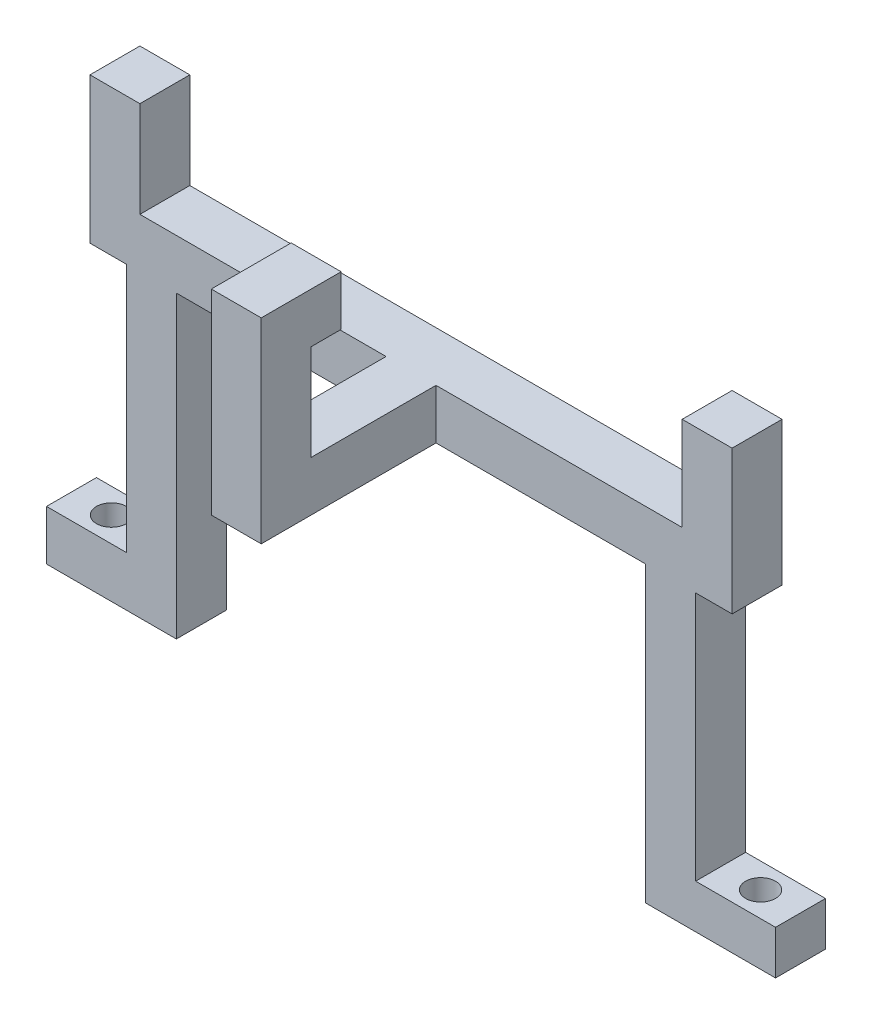
SolidWorks part; units mm, degrees
ref_plane "Front Plane" through (0, 0, 0) normal (0, 0, 1) x (1, 0, 0)
ref_plane "Top Plane" through (0, 0, 0) normal (0, 1, 0) x (1, 0, 0)
ref_plane "Right Plane" through (0, 0, 0) normal (1, 0, 0) x (0, 0, -1)
sketch "Sketch1" plane through (0, 0, 0) normal (0, 0, 1) x (1, 0, 0)
  line L0 (0, 0) -> (0, 25)
  line L1 (-3.65, 25) -> (-3.65, 39.6)
  line L2 (0, 25) -> (-3.65, 25)
  line L3 (-3.65, 39.6) -> (1.35, 39.6)
  line L4 (1.35, 30) -> (5, 30)
  line L8 (1.35, 39.6) -> (1.35, 30)
  line L9 (5, 30) -> (5, -5)
  line L10 (5, -5) -> (-8, -5)
  line L11 (-8, -5) -> (-8, 0)
  line L12 (-8, 0) -> (0, 0)
  dimension "D1" = 5
  dimension "D2" = 25
  dimension "D3" = 5
  dimension "D4" = 3.65
  dimension "D5" = 5
  dimension "D6" = 35
  dimension "D7" = 9.6
  dimension "D8" = 5
  dimension "D9" = 8
extrude "Boss-Extrude1" add sketch "Sketch1" along normal blind 5
sketch "Sketch2" plane through (0, 0, 0) normal (0, 1, 0) x (1, 0, 0)
  line L0 (-4, 0) -> (-4, -5) construction
  line L1 (0, 0) -> (-8, 0) construction
  line L2 (0, -5) -> (-8, -5) construction
  line L3 (-4, -5) -> (-4, 0) construction
  circle A0 centre (-4, -2.5) radius 1.5
extrude "Cut-Extrude1" cut sketch "Sketch2" against normal through all
sketch "Sketch3" plane through (5, 0, 0) normal (1, 0, 0) x (0, 0, -1)
  line L0 (-5, 30) -> (-5, 25)
  line L1 (-5, -5) -> (-5, 30) construction
  line L2 (-5, 25) -> (0, 25)
  line L3 (0, -5) -> (0, 30) construction
  line L4 (0, 25) -> (0, 30)
  line L5 (0, 30) -> (-5, 30)
  dimension "D1" = 5
  dimension "D2" = 5
extrude "Boss-Extrude2" add sketch "Sketch3" along normal blind 47
sketch "Sketch4" plane through (0, 0, 0) normal (0, 0, -1) x (-1, 0, 0)
  line L0 (-52, 30) -> (-55.65, 30)
  line L1 (-55.65, 30) -> (-55.65, 39.3793)
  line L2 (-55.65, 39.3793) -> (-60.65, 39.3793)
  line L3 (-60.65, 39.3793) -> (-60.65, 25)
  line L4 (-60.65, 25) -> (-57, 25)
  line L5 (-57, 25) -> (-57, 0)
  line L6 (-57, 0) -> (-65, 0)
  line L7 (-65, 0) -> (-65, -4.3959)
  line L8 (-65, -4.3959) -> (-52, -4.3959)
  line L9 (-52, -4.3959) -> (-52, 25)
  line L10 (-52, 25) -> (-5, 25) construction
  line L11 (-52, 25) -> (-52, 30) construction
  line L12 (-52, 25) -> (-52, 30)
  line L13 (-5, -5) -> (-5, 25) construction
  line L14 (3.65, 39.6) -> (3.65, 25) construction
  line L16 (0, 25) -> (0, 0) construction
  dimension "D1" = 8.65
  dimension "D2" = 8.65
  dimension "D3" = 5
  dimension "D4" = 5
  dimension "D5" = 5
  dimension "D6" = 13
extrude "Boss-Extrude3" add sketch "Sketch4" against normal blind 5
sketch "Sketch5" plane through (0, 0, 0) normal (0, 1, 0) x (1, 0, 0)
  line L3 (57, -5) -> (57, 0) construction
  circle A0 centre (61, -2.5) radius 1.5
  dimension "D1" = 4
extrude "Cut-Extrude2" cut sketch "Sketch5" against normal through all
sketch "Sketch7" plane through (0, 0, 5) normal (0, 0, 1) x (1, 0, 0)
  line L0 (28.5, 30) -> (28.5, 25) construction
  line L1 (55.65, 30) -> (1.35, 30) construction
  line L2 (52, 25) -> (5, 25) construction
  line L3 (28.5, 30) -> (31, 30)
  line L4 (31, 30) -> (31, 25)
  line L5 (31, 25) -> (26, 25)
  line L6 (26, 25) -> (26, 30)
  line L7 (26, 30) -> (28.5, 30)
  dimension "D1" = 2.5
  dimension "D2" = 2.5
extrude "Boss-Extrude4" add sketch "Sketch7" along normal blind 12.5
sketch "Sketch10" plane through (0, 25, 0) normal (0, -1, 0) x (-1, 0, 0)
  line L0 (-31, -17.5) -> (-31, -22.5)
  line L1 (-31, -22.5) -> (-26, -22.5)
  line L2 (-26, -22.5) -> (-26, -17.5)
  line L11 (-5, -5) -> (-5, 0)
  line L12 (-5, 0) -> (-52, 0)
  line L13 (-52, 0) -> (-52, -5)
  line L14 (-52, -5) -> (-31, -5)
  line L15 (-31, -5) -> (-31, -17.5)
  line L16 (-31, -17.5) -> (-26, -17.5)
  line L17 (-26, -17.5) -> (-26, -5)
  line L18 (-26, -5) -> (-5, -5)
  line L24 (-31, -17.5) -> (-26, -17.5)
  dimension "D1" = 5
  dimension "D2" = 5
  dimension "D3" = 0
extrude "Boss-Extrude5" add sketch "Sketch10" against normal blind 14.6
sketch "Sketch11" plane through (0, 39.6, 0) normal (0, 1, 0) x (1, 0, 0)
  line L0 (26, -17.5) -> (26, -14.5)
  line L1 (26, -14.5) -> (31, -14.5)
  line L2 (31, -14.5) -> (31, -22.5)
  line L3 (31, -22.5) -> (26, -22.5)
  line L4 (26, -22.5) -> (26, -17.5)
  dimension "D1" = 8
extrude "Boss-Extrude6" add sketch "Sketch11" along normal blind 5
